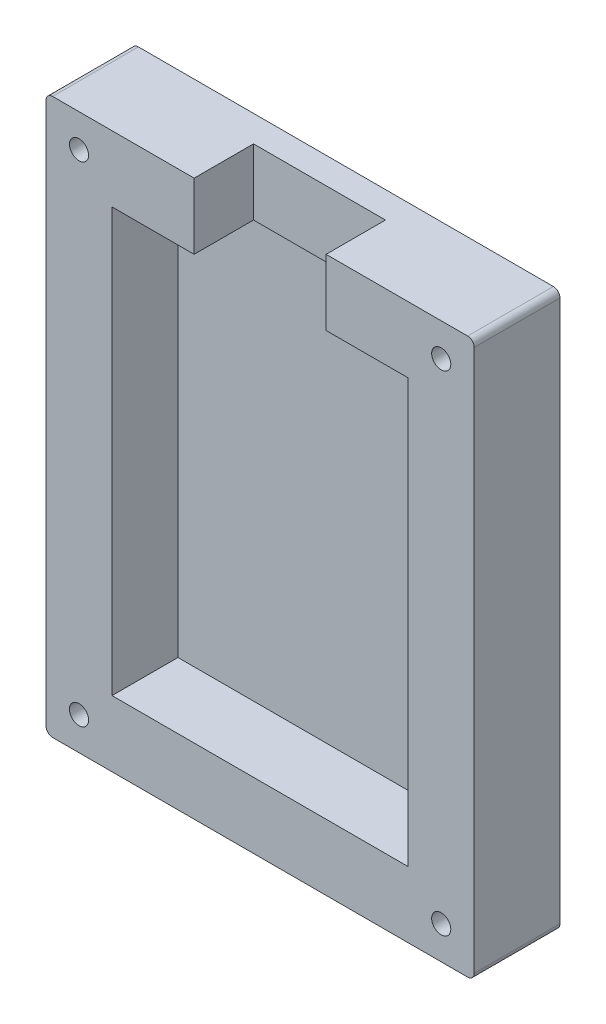
SolidWorks part; units mm, degrees
ref_plane "Front Plane" through (0, 0, 0) normal (0, 0, 1) x (1, 0, 0)
ref_plane "Top Plane" through (0, 0, 0) normal (0, 1, 0) x (1, 0, 0)
ref_plane "Right Plane" through (0, 0, 0) normal (1, 0, 0) x (0, 0, -1)
sketch "Esquisse2" plane through (0, 0, 0) normal (0, 0, 1) x (1, 0, 0)
  line L0 (-32.2354, -23.0898) -> (12.6646, -23.0898)
  line L1 (12.6646, -23.0898) -> (12.6646, 41.0602)
  line L2 (12.6646, 41.0602) -> (-32.2354, 41.0602)
  line L3 (-32.2354, 41.0602) -> (-32.2354, -23.0898)
  line L4 (-42.2354, -33.0898) -> (22.6646, -33.0898)
  line L5 (-42.2354, -33.0898) -> (-42.2354, 51.0599)
  line L6 (-42.2354, 51.0599) -> (22.6646, 51.0599)
  line L7 (22.6646, 51.0599) -> (22.6646, -33.0898)
  circle A0 centre (17.6646, 46.0599) radius 1.45
  circle A1 centre (-37.2354, 46.0599) radius 1.45
  circle A2 centre (-37.2354, -28.0898) radius 1.45
  circle A3 centre (17.6646, -28.0898) radius 1.45
  dimension "D8" = 2.9
  dimension "D10" = 2.9
  dimension "D12" = 2.9
  dimension "D13" = 2.9
  dimension "D1" = 64.15
  dimension "D2" = 44.9
  dimension "D3" = 10
  dimension "D4" = 10
  dimension "D5" = 10
  dimension "D6" = 5
  dimension "D7" = 5
  dimension "D9" = 5
  dimension "D11" = 5
extrude "Boss.-Extru.3" add sketch "Esquisse2" along normal blind 13
sketch "Esquisse6" plane through (0, 0, 0) normal (0, 0, 1) x (1, 0, 0)
  line L0 (12.6646, 41.0602) -> (12.6646, -23.0898)
  line L1 (12.6646, -23.0898) -> (-32.2354, -23.0898)
  line L2 (-32.2354, -23.0898) -> (-32.2354, 41.0602)
  line L3 (-32.2354, 41.0602) -> (12.6646, 41.0602)
extrude "Boss.-Extru.4" add sketch "Esquisse6" along normal blind 3
sketch "Esquisse8" plane through (0, 41.0602, 0) normal (0, -1, 0) x (1, 0, 0)
  line L0 (-42.2354, 0) -> (22.6646, 0) construction
  line L1 (-19.7854, 4) -> (0.2146, 4)
  line L2 (-19.7854, 4) -> (-19.7854, 13)
  line L3 (-19.7854, 13) -> (0.2146, 13)
  line L4 (0.2146, 4) -> (0.2146, 13)
  line L5 (12.6646, 13) -> (-32.2354, 13) construction
  point P4 (-9.7854, 0)
  dimension "D1" = 9
  dimension "D2" = 20
  dimension "D3" = 10
  dimension "D4" = 9
extrude "Enlèv. mat.-Extru.2" cut sketch "Esquisse8" against normal blind 10
fillet "Congé1" radius 1 1 edges at (-42.2354, 51.0599, 6.5)
fillet "Congé2" radius 1 1 edges at (-42.2354, -33.0898, 6.5)
fillet "Congé3" radius 1 1 edges at (22.6646, -33.0898, 6.5)
fillet "Congé4" radius 1 1 edges at (22.6646, 51.0599, 6.5)
